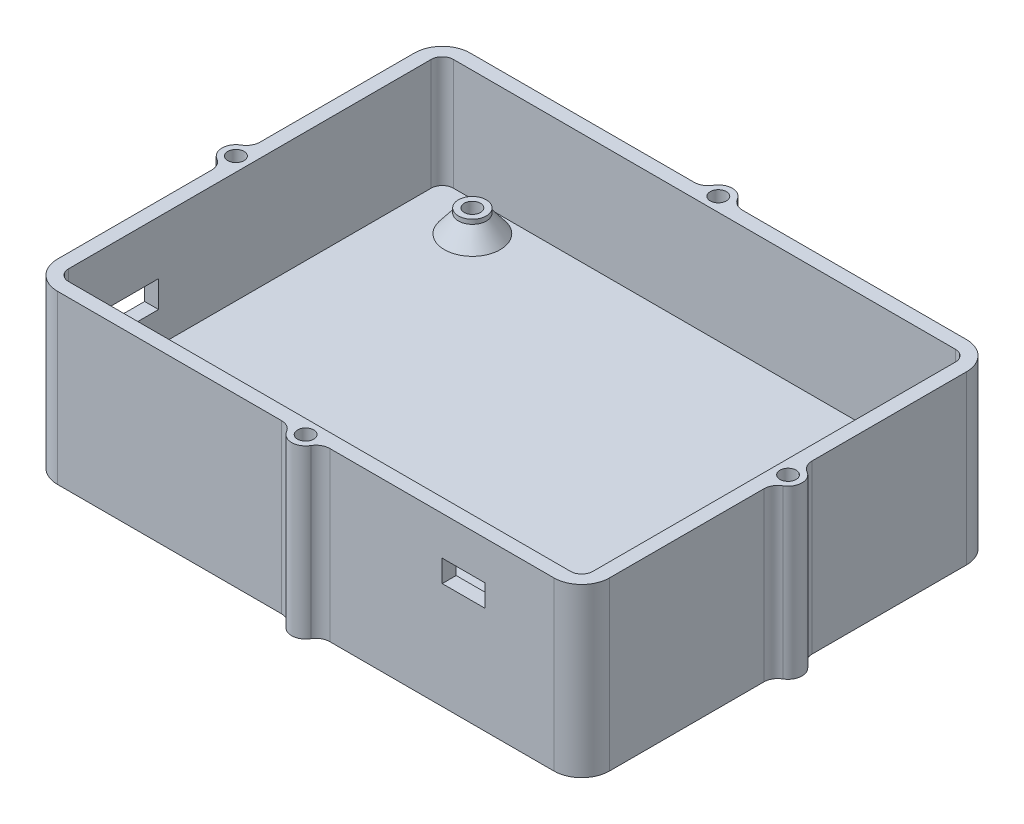
SolidWorks part; units mm, degrees
ref_plane "Front Plane" through (0, 0, 0) normal (0, 0, 1) x (1, 0, 0)
ref_plane "Top Plane" through (0, 0, 0) normal (0, 1, 0) x (1, 0, 0)
ref_plane "Right Plane" through (0, 0, 0) normal (1, 0, 0) x (0, 0, -1)
sketch "Sketch1" plane through (0, 0, 0) normal (0, 1, 0) x (1, 0, 0)
  line L1 (-49.5, 37) -> (49.5, 37)
  line L2 (-49.5, 37) -> (-49.5, -37)
  line L3 (-49.5, -37) -> (49.5, -37)
  line L4 (49.5, 37) -> (49.5, -37)
  line L5 (-49.5, 37) -> (49.5, -37) construction
  line L6 (-49.5, -37) -> (49.5, 37) construction
  point P0 (0, 0)
  dimension "D1" = 99
  dimension "D2" = 74
extrude "Boss-Extrude1" add sketch "Sketch1" along normal blind 30
sketch "Sketch2" plane through (0, 30, 0) normal (0, 1, 0) x (1, 0, 0)
  line L1 (-47, 34.5) -> (47, 34.5)
  line L2 (-47, 34.5) -> (-47, -34.5)
  line L3 (-47, -34.5) -> (47, -34.5)
  line L4 (47, 34.5) -> (47, -34.5)
  line L5 (-47, 34.5) -> (47, -34.5) construction
  line L6 (-47, -34.5) -> (47, 34.5) construction
  point P0 (0, 0)
  dimension "D1" = 94
  dimension "D2" = 69
extrude "Cut-Extrude1" cut sketch "Sketch2" against normal blind 20
fillet "Fillet2" radius 5 4 edges at (49.5, 15, 37) (-49.5, 15, 37) (-49.5, 15, -37) (49.5, 15, -37)
fillet "Fillet3" radius 2 4 edges at (47, 20, 34.5) (47, 20, -34.5) (-47, 20, -34.5) (-47, 20, 34.5)
sketch "Sketch3" plane through (0, 10, 0) normal (0, 1, 0) x (1, 0, 0)
  line L0 (45.78, -32.9565) -> (-45.78, -32.9565) construction
  line L1 (45.78, -32.9565) -> (45.78, 32.9565) construction
  line L2 (45.78, 32.9565) -> (-45.78, 32.9565) construction
  line L3 (-45.78, -32.9565) -> (-45.78, 32.9565) construction
  line L6 (45.78, -32.9565) -> (-45.78, 32.9565) construction
  line L7 (45.78, 32.9565) -> (-45.78, -32.9565) construction
  circle A5 centre (-36.255, 29.1465) radius 2.5
  circle A6 centre (41.469, 29.1465) radius 2.5
  circle A7 centre (41.471, -28.8925) radius 2.5
  circle A8 centre (-36.763, -28.8925) radius 2.5
  point P6 (0, 0)
  dimension "D5" = 9.017
  dimension "D11" = 61.849
  dimension "D1" = 5
  dimension "D9" = 3.81
  dimension "D2" = 9.525
  dimension "D6" = 87.249
  dimension "D7" = 65.913
  dimension "D8" = 91.56
  dimension "D10" = 87.251
  dimension "D3" = 3.81
  dimension "D4" = 61.849
extrude "Boss-Extrude2" add sketch "Sketch3" along normal blind 4
sketch "Sketch8" plane through (0, 14, 0) normal (0, 1, 0) x (1, 0, 0)
  circle A0 centre (-36.255, 29.1465) radius 1.45
  circle A1 centre (-36.255, 29.1465) radius 2.5 construction
  circle A2 centre (-36.763, -28.8925) radius 1.45
  circle A3 centre (41.469, 29.1465) radius 1.45
  circle A4 centre (41.471, -28.8925) radius 1.45
  circle A5 centre (-36.763, -28.8925) radius 2.5 construction
  circle A7 centre (41.471, -28.8925) radius 2.5 construction
  circle A8 centre (41.469, 29.1465) radius 2.5 construction
  dimension "D1" = 2.9
extrude "Cut-Extrude4" cut sketch "Sketch8" against normal blind 5
chamfer "Chamfer1" distance 2.5 angle 52 1 edges at (-36.763, 10, 31.3925)
chamfer "Chamfer2" distance 2.5 angle 52 1 edges at (41.471, 10, 31.3925)
chamfer "Chamfer3" distance 2.5 angle 52 1 edges at (-36.255, 10, -26.6465)
chamfer "Chamfer4" distance 2.5 angle 52 1 edges at (41.469, 10, -26.6465)
sketch "Sketch10" plane through (0, 0, 0) normal (0, -1, 0) x (1, 0, 0)
  line L0 (-44.5, 37) -> (44.5, 37) construction
  line L1 (44.5, -37) -> (-44.5, -37) construction
  line L2 (-49.5, -32) -> (-49.5, 32) construction
  line L3 (49.5, 32) -> (49.5, -32) construction
  line L4 (-2.5, 37) -> (2.5, 37)
  line L5 (-49.5, -2.5) -> (-49.5, 2.5)
  line L6 (-2.5, -37) -> (2.5, -37)
  line L7 (49.5, 2.5) -> (49.5, -2.5)
  arc A0 (-2.5, 37) -> (2.5, 37) centre (0, 37) cw
  arc A1 (-2.5, -37) -> (2.5, -37) centre (0, -37) ccw
  arc A2 (-49.5, 2.5) -> (-49.5, -2.5) centre (-49.5, 0) ccw
  arc A3 (49.5, -2.5) -> (49.5, 2.5) centre (49.5, 0) ccw
extrude "Boss-Extrude3" add sketch "Sketch10" against normal up to surface (30 mm away) up to face at (0, 30, 0)
sketch "Sketch11" plane through (0, 30, 0) normal (0, 1, 0) x (1, 0, 0)
  circle A0 centre (0, 37) radius 1.45
  circle A2 centre (-49.5, 0) radius 1.45
  circle A3 centre (0, -37) radius 1.45
  circle A4 centre (49.5, 0) radius 1.45
extrude "Cut-Extrude5" cut sketch "Sketch11" against normal blind 6
fillet "Fillet5" radius 2.5 8 edges at (49.5, 15, -2.5) (49.5, 15, 2.5) (-2.5, 15, -37) (2.5, 15, -37) (-49.5, 15, 2.5) (-49.5, 15, -2.5) (2.5, 15, 37) (-2.5, 15, 37)
sketch "Sketch13" plane through (-49.5, 0, 0) normal (-1, 0, 0) x (0, 0, 1)
  line L0 (16.3741, 20.4) -> (26.3741, 20.4)
  line L1 (16.3741, 20.4) -> (16.3741, 15.6)
  line L2 (16.3741, 15.6) -> (26.3741, 15.6)
  line L3 (26.3741, 20.4) -> (26.3741, 15.6)
  line L4 (16.3741, 20.4) -> (26.3741, 15.6) construction
  line L5 (16.3741, 15.6) -> (26.3741, 20.4) construction
  line L6 (4.3301, 0) -> (32, 0) construction
  line L9 (37, 0) -> (37, 30) construction
  point P0 (21.3741, 18)
  dimension "D1" = 4.8
  dimension "D2" = 20.4
  dimension "D3" = 10
  dimension "D4" = 10.6259
extrude "Cut-Extrude7" cut sketch "Sketch13" against normal up to surface (2.5 mm away) up to face at (-47, 20, 0)
sketch "Sketch14" plane through (0, 0, 37) normal (0, 0, 1) x (1, 0, 0)
  line L0 (49.5, 0) -> (49.5, 30) construction
  line L1 (24.4881, 23.05) -> (32.1881, 23.05)
  line L2 (24.4881, 23.05) -> (24.4881, 19.1)
  line L3 (24.4881, 19.1) -> (32.1881, 19.1)
  line L4 (32.1881, 23.05) -> (32.1881, 19.1)
  line L5 (24.4881, 23.05) -> (32.1881, 19.1) construction
  line L6 (24.4881, 19.1) -> (32.1881, 23.05) construction
  line L7 (4.3301, 0) -> (44.5, 0) construction
  point P0 (28.3381, 21.075)
  dimension "D1" = 25.0119
  dimension "D2" = 7.7
  dimension "D3" = 3.95
  dimension "D4" = 23.05
extrude "Cut-Extrude8" cut sketch "Sketch14" against normal up to surface (2.5 mm away) up to face at (0, 20, 34.5)
